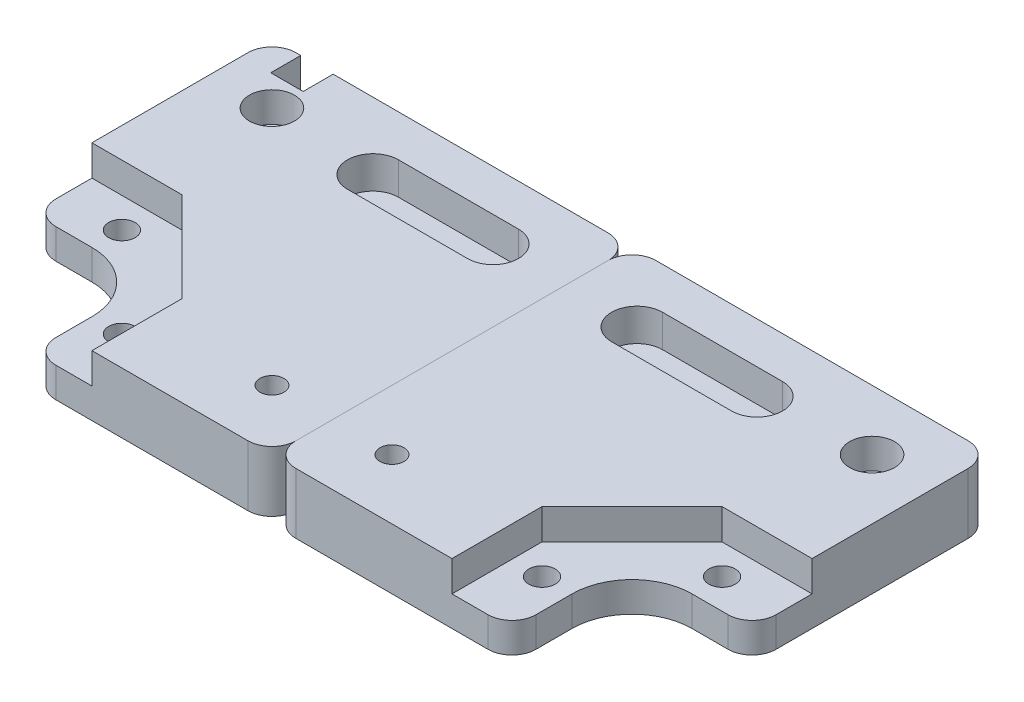
SolidWorks part; units mm, degrees
ref_plane "Front Plane" through (0, 0, 0) normal (0, 0, 1) x (1, 0, 0)
ref_plane "Top Plane" through (0, 0, 0) normal (0, 1, 0) x (1, 0, 0)
ref_plane "Right Plane" through (0, 0, 0) normal (1, 0, 0) x (0, 0, -1)
sketch "Sketch1" plane through (0, 0, 0) normal (0, 1, 0) x (1, 0, 0)
  line L0 (0, 0) -> (0, 20)
  line L1 (0, 0) -> (-40, 0)
  line L2 (20, 20) -> (20, 60)
  line L3 (20, 60) -> (-40, 60)
  line L4 (-40, 0) -> (-40, 60)
  line L5 (0, 20) -> (20, 20)
  line L6 (-10, 60) -> (-10, 0) construction
  line L7 (-40, 30) -> (20, 30) construction
  line L8 (20, 40) -> (0, 40) construction
  line L9 (0, 40) -> (-20, 20) construction
  line L10 (-20, 20) -> (-20, 0) construction
  line L15 (-10, 30) -> (0, 20) construction
  circle A0 centre (-28, 48.8332) radius 2.5 construction
  circle A1 centre (10, 25) radius 2.2
  circle A2 centre (-5, 10) radius 2.2
  point P18 (-10, 30)
  point P60 (20, 40)
  dimension "D4" = 11.1668
  dimension "D5" = 5
  dimension "D8" = 5
  dimension "D9" = 4.4
  dimension "D1" = 60
  dimension "D2" = 40
  dimension "D3" = 12
  dimension "D6" = 20
  dimension "D7" = 10
extrude "Boss-Extrude1" add sketch "Sketch1" along normal blind 10.1
sketch "Sketch4" plane through (0, 10.1, 0) normal (0, 1, 0) x (1, 0, 0)
  line L0 (-28, 53.0832) -> (-8, 53.0832)
  line L1 (-28, 44.5832) -> (-8, 44.5832)
  line L2 (-28, 53.0832) -> (-28, 44.5832) construction
  line L3 (-8, 53.0832) -> (-8, 44.5832) construction
  line L5 (-40, 60) -> (-40, 0) construction
  line L6 (-28, 44.5832) -> (-28, 53.0832) construction
  arc A1 (-28, 53.0832) -> (-28, 44.5832) centre (-28, 48.8332) ccw
  arc A2 (-8, 44.5832) -> (-8, 53.0832) centre (-8, 48.8332) ccw
  arc A3 (-8, 53.0832) -> (-8, 44.5832) centre (-8, 48.8332) ccw construction
  arc A4 (-28, 44.5832) -> (-28, 53.0832) centre (-28, 48.8332) ccw construction
  point P14 (-28, 48.8332)
  dimension "D1" = 8.5
  dimension "D2" = 20
extrude "Cut-Extrude2" cut sketch "Sketch4" against normal blind 5.4
sketch "Sketch7" plane through (0, 10.1, 0) normal (0, 1, 0) x (1, 0, 0)
  line L0 (0, 0) -> (20, 0) construction
  line L1 (20, 0) -> (20, 20) construction
  line L2 (20, 20) -> (20, 60) construction
  line L3 (0, 0) -> (0, 20) construction
  line L4 (20, 0) -> (-10, 0)
  line L5 (20, 0) -> (20, 30)
  line L6 (20, 30) -> (5, 30)
  line L7 (-10, 0) -> (-10, 15)
  line L8 (-10, 15) -> (5, 30)
  line L9 (-10, 15) -> (-10, 30) construction
  line L10 (5, 30) -> (-10, 30) construction
  dimension "D1" = 10
  dimension "D2" = 15
extrude "Cut-Extrude4" cut sketch "Sketch7" against normal blind 5.1
sketch "Sketch9" plane through (0, 10.1, 0) normal (0, 1, 0) x (1, 0, 0)
  line L0 (0, 10) -> (-40, 10) construction
  line L1 (0, 0) -> (0, 20) construction
  line L2 (-40, 60) -> (-40, 0) construction
  line L3 (-40, 60) -> (0, 20) construction
  circle A0 centre (-30, 10) radius 2
  circle A1 centre (10, 50) radius 2
  dimension "D2" = 4
  dimension "D1" = 10
extrude "Cut-Extrude5" cut sketch "Sketch9" against normal through all
sketch "Sketch10" plane through (0, 10.1, 0) normal (0, 1, 0) x (1, 0, 0)
  circle A0 centre (10, 50) radius 3.75
  dimension "D1" = 7.5
extrude "Cut-Extrude6" cut sketch "Sketch10" against normal blind 5
fillet "Fillet2" radius 10 1 edges at (0, 2.5, -20)
fillet "Fillet3" radius 4 5 edges at (-40, 5.05, 0) (-40, 5.05, -60) (0, 2.5, 0) (20, 2.5, -20) (20, 5.05, -60)
mirror "Mirror1" about plane through (-40, 10.1, 0) normal (1, 0, 0) of bodies 108
sketch "Sketch11" plane through (0, 0, -60) normal (0, 0, -1) x (-1, 0, 0)
  line L0 (96, 10.1) -> (96, 0) construction
  line L1 (96, 1.8) -> (89, 1.8)
  line L2 (96, 1.8) -> (96, 5)
  line L3 (96, 5) -> (95.2, 5)
  line L4 (89, 1.8) -> (89, 5)
  line L5 (92.5, 1.8) -> (92.5, 10.1) construction
  line L6 (96, 10.1) -> (44, 10.1) construction
  line L7 (89.8, 5) -> (89, 5)
  line L8 (89.8, 10.1) -> (95.2, 10.1)
  line L9 (89.8, 10.1) -> (89.8, 5)
  line L11 (95.2, 10.1) -> (95.2, 5)
  point P14 (92.5, 10.1)
  dimension "D1" = 2.7
  dimension "D2" = 3.2
  dimension "D3" = 8.3
  dimension "D4" = 7
extrude "Cut-Extrude7" cut sketch "Sketch11" against normal blind 5
